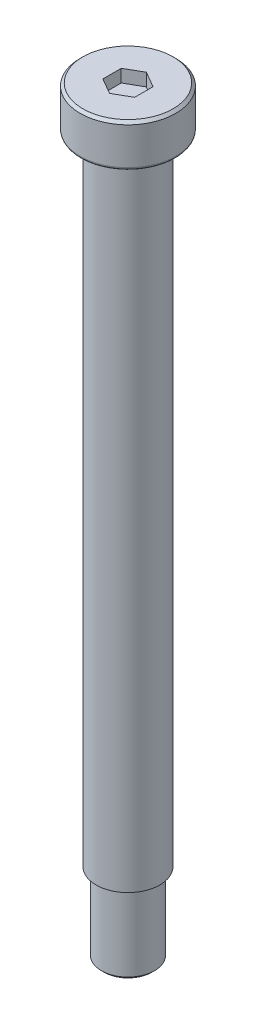
SolidWorks part; units mm, degrees
material "Plain Carbon Steel"
ref_plane "Front Plane" through (0, 0, 0) normal (0, 0, 1) x (1, 0, 0)
ref_plane "Top Plane" through (0, 0, 0) normal (0, 1, 0) x (1, 0, 0)
ref_plane "Right Plane" through (0, 0, 0) normal (1, 0, 0) x (0, 0, -1)
sketch "Sketch1" plane through (0, 0, 0) normal (0, 0, 1) x (1, 0, 0)
  line L0 (0, 0) -> (9, 0)
  line L1 (9, 0) -> (9, -8)
  line L2 (9, -8) -> (5.75, -8)
  line L3 (5.75, -8) -> (5.75, -8.5)
  line L4 (5.75, -8.5) -> (6, -8.5)
  line L5 (6, -8.5) -> (6, -128)
  line L6 (6, -128) -> (5, -128)
  line L7 (5, -128) -> (5, -143)
  line L8 (5, -143) -> (0, -143)
  line L9 (0, -143) -> (0, 0)
  line L10 (0, 5) -> (0, -148) construction
  dimension "D1" = 5
  dimension "D2" = 5
  dimension "D3" = 10
  dimension "D4" = 12
  dimension "D5" = 0.25
  dimension "D6" = 18
  dimension "Length" = 120
  dimension "D8" = 8
  dimension "D9" = 0.5
  dimension "D10" = 15
revolve "Revolve1" add sketch "Sketch1" angle 360 about L10
sketch "Sketch2" plane through (0, 0, 0) normal (0, 1, 0) x (1, 0, 0)
  line L1 (0, -3.4641) -> (3, -1.7321)
  line L2 (3, -1.7321) -> (3, 1.7321)
  line L3 (3, 1.7321) -> (0, 3.4641)
  line L4 (0, 3.4641) -> (-3, 1.7321)
  line L5 (-3, 1.7321) -> (-3, -1.7321)
  line L6 (-3, -1.7321) -> (0, -3.4641)
  circle A0 centre (0, 0) radius 3 construction
  dimension "D1" = 6
extrude "Cut-Extrude1" cut sketch "Sketch2" against normal blind 2.4
chamfer "Chamfer1" distance 0.5 angle 45 1 edges at (-9, 0, 0)
fillet "Fillet1" radius 0.5 1 edges at (-9, -8, 0)
chamfer "Chamfer2" distance 0.5 angle 45 1 edges at (-5, -143, 0)
